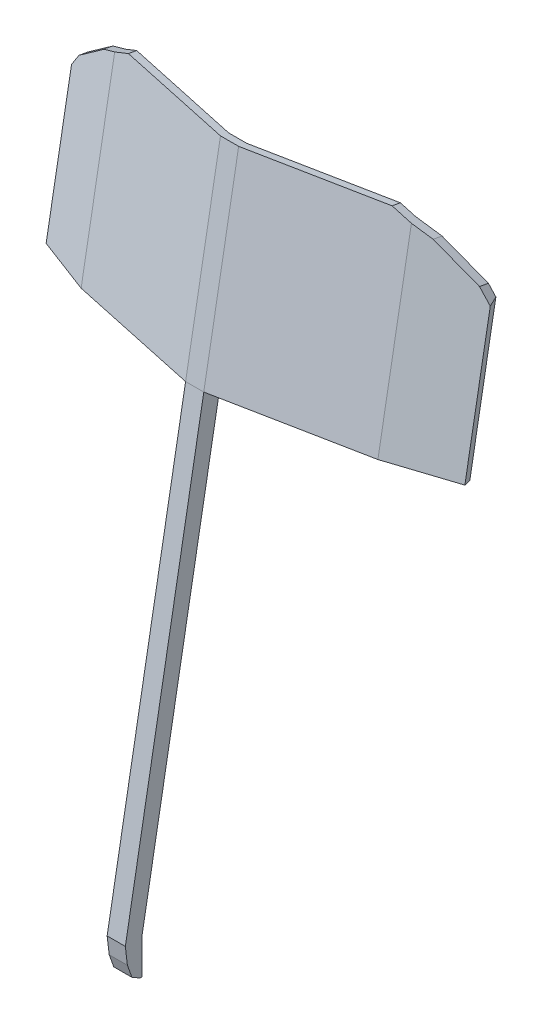
SolidWorks part; units mm, degrees
ref_plane "Front Plane" through (0, 0, 0) normal (0, 0, 1) x (1, 0, 0)
ref_plane "Top Plane" through (0, 0, 0) normal (0, 1, 0) x (1, 0, 0)
ref_plane "Right Plane" through (0, 0, 0) normal (1, 0, 0) x (0, 0, -1)
sketch "Sketch3" plane through (0, 0, 0) normal (0, 0, 1) x (1, 0, 0)
  line L0 (-5.5, -10.5) -> (-5.5, 10.5)
  line L2 (-5.5, 10.5) -> (5.5, 10.5)
  line L3 (5.5, 10.5) -> (5.5, -10.5)
  line L4 (5.5, -10.5) -> (-5.5, -10.5)
  dimension "D1" = 11
  dimension "D2" = 21
  dimension "D3" = 5.5
  dimension "D4" = 10.5
extrude "Boss-Extrude1" add sketch "Sketch3" along normal blind 10
sketch "Sketch5" plane through (0, 0, 0) normal (0, 0, 1) x (1, 0, 0)
  line L0 (0, 0) -> (0, 1.5)
  line L1 (0, 1.5) -> (-2, 1.5)
  line L2 (-2, 1.5) -> (-2, -1.5)
  line L3 (-2, -1.5) -> (2, -1.5)
  line L4 (2, -1.5) -> (2, 1.5)
  line L5 (2, 1.5) -> (0, 1.5)
  dimension "D1" = 2
  dimension "D2" = 4
  dimension "D3" = 3
  dimension "D4" = 1.5
extrude "Cut-Extrude1" cut sketch "Sketch5" along normal blind 8 contours L1 L2 L3 L4 L5
sketch "Sketch6" plane through (0, 0, 0) normal (1, 0, 0) x (0, 0, -1)
  line L1 (-10, -10.5) -> (0, -10.5) construction
  line L2 (-1.0867, -10.5) -> (-6.0116, -7.6935)
  line L3 (-6.0116, -7.6935) -> (-8.7536, 0)
  line L4 (-8.7536, 0) -> (-10, 10.5)
  line L5 (0, 0) -> (-8.7536, 0)
  line L6 (-10, 10.5) -> (-10, -10.5)
  line L8 (-1.0867, -10.5) -> (-1.0867, -10.7607)
  line L9 (-1.0867, -10.7607) -> (-10, -11.3245)
  line L10 (-10, -11.3245) -> (-10, -10.5)
  point P0 (-10, -10.5)
extrude "Cut-Extrude5" cut sketch "Sketch6" against normal blind 8 and the other way blind 8 contours L3 L2 L8 L9 L10 L6 L4
sketch "Sketch7" plane through (0, 0, 0) normal (1, 0, 0) x (0, 0, -1)
  line L0 (0, -10.5) -> (86.8528, 255.9971)
  dimension "D1" = 280.2929
sketch "Sketch18" plane through (0, 0, 0) normal (1, 0, 0) x (0, 0, -1)
  line L0 (0, 10.5) -> (47.2746, 275.3165)
  line L1 (-10, 10.5) -> (0, 10.5)
  line L2 (47.2746, 275.3165) -> (37.4302, 277.0739)
  line L7 (-10, 10.5) -> (37.4302, 277.0739)
  point P3 (-10, 10.5)
  point P5 (48.8344, 290.4231)
  point P7 (0, 0)
  point P8 (47.2746, 277.0739)
  dimension "D2" = 10
extrude "Boss-Extrude2" add sketch "Sketch18" along normal blind 5.5 and the other way blind 5.5
ref_plane "Plane1" through (0, 274.9922, -49.0911) normal (0, 0.9844, -0.1757) x (1, 0, 0)
sketch "Sketch20" plane through (0, 274.9922, -49.0911) normal (0, 0.9844, -0.1757) x (1, 0, 0)
  line L0 (5.5, -11.8453) -> (89.7224, 9.5434)
  line L8 (5.5, -6.8453) -> (87.652, 14.0946)
  line L11 (0, -57.6018) -> (0, 57.6018) construction
  line L13 (-5.5, -6.8453) -> (-87.652, 14.0946)
  line L15 (-5.5, -11.8453) -> (-89.7224, 9.5434)
  line L18 (-5.5, -6.8453) -> (5.5, -6.8453)
  line L19 (-5.5, -11.8453) -> (5.5, -11.8453)
  line L20 (-126.5989, 25.507) -> (-124.9381, 30.2278)
  line L21 (126.5989, 25.507) -> (124.9381, 30.2278)
  line L22 (87.652, 14.0946) -> (124.9381, 30.2278)
  line L23 (89.7224, 9.5434) -> (126.5989, 25.507)
  line L24 (-126.5989, 25.507) -> (-89.7224, 9.5434)
  line L25 (-124.9381, 30.2278) -> (-87.652, 14.0946)
extrude "Boss-Extrude6" add sketch "Sketch20" along normal blind 120 contours L0 L23 L21 L22 L8 L18 L13 L25 L20 L24 L15 L19
ref_plane "Plane2" through (0, 3.8391, 21.5053) normal (0, 0.1757, 0.9844) x (1, 0, 0)
sketch "Sketch23" plane through (0, 3.8391, 21.5053) normal (0, 0.1757, 0.9844) x (1, 0, 0)
  line L0 (126.5989, 399.3397) -> (126.5989, 279.3397) construction
  line L1 (-126.5989, 399.3397) -> (-126.5989, 279.3397) construction
  line L2 (-5.5, 419.3397) -> (-1.5592, 421.5729)
  line L4 (-5.5, 399.3397) -> (-89.7224, 399.3397) construction
  line L5 (-5.5, 419.3397) -> (-79.7224, 399.3397)
  line L6 (-99.4802, 390.2239) -> (-79.7224, 399.3397)
  line L7 (-99.4802, 390.2239) -> (-121.1009, 374.4503)
  line L8 (-121.1009, 374.4503) -> (-131.6894, 359.5828)
  line L9 (-131.6894, 359.5828) -> (-185.5429, 339.3397)
  line L10 (-185.5429, 339.3397) -> (-131.6894, 409.1115)
  line L11 (-131.6894, 409.1115) -> (-45.7701, 435.5591)
  line L13 (0, -60.4655) -> (0, 60.4655) construction
  line L14 (-1.5592, 421.5729) -> (-44.3515, 435.5591)
  line L15 (-44.3515, 435.5591) -> (-45.7701, 435.5591)
  line L16 (5.5, 419.3397) -> (79.7224, 399.3397)
  line L17 (99.4802, 390.2239) -> (79.7224, 399.3397)
  line L18 (99.4802, 390.2239) -> (121.1009, 374.4503)
  line L19 (121.1009, 374.4503) -> (131.6894, 359.5828)
  line L20 (131.6894, 359.5828) -> (185.5429, 339.3397)
  line L21 (185.5429, 339.3397) -> (131.6894, 409.1115)
  line L22 (131.6894, 409.1115) -> (45.7701, 435.5591)
  line L23 (44.3515, 435.5591) -> (45.7701, 435.5591)
  line L24 (1.5592, 421.5729) -> (44.3515, 435.5591)
  line L25 (5.5, 419.3397) -> (1.5592, 421.5729)
  point P0 (-5.5, 399.3397)
  point P1 (5.5, 399.3397)
  point P3 (89.7224, 399.3397)
  point P5 (126.5989, 339.3397)
  point P7 (-126.5989, 339.3397)
  point P10 (-89.7224, 399.3397)
  point P21 (-79.7224, 399.3397)
extrude "Cut-Extrude6" cut sketch "Sketch23" against normal blind 120
